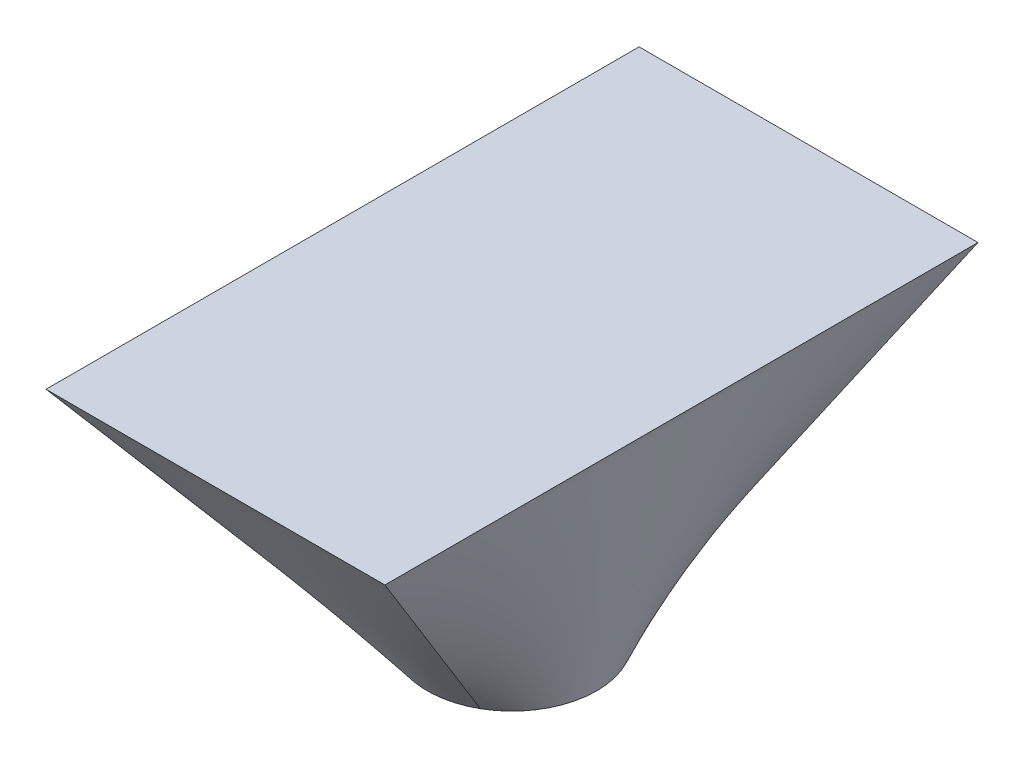
SolidWorks part; units mm, degrees
ref_plane "Front Plane" through (0, 0, 0) normal (0, 0, 1) x (1, 0, 0)
ref_plane "Top Plane" through (0, 0, 0) normal (0, 1, 0) x (1, 0, 0)
ref_plane "Right Plane" through (0, 0, 0) normal (1, 0, 0) x (0, 0, -1)
sketch "Sketch1" plane through (0, 0, 0) normal (0, 1, 0) x (1, 0, 0)
  circle A0 centre (0, 0) radius 3
ref_plane "Plane1" through (0, 10, 0) normal (0, 1, 0) x (1, 0, 0)
sketch "Sketch2" plane through (0, 10, 0) normal (0, 1, 0) x (1, 0, 0)
  line L1 (-6, -10.5) -> (6, -10.5)
  line L2 (-6, -10.5) -> (-6, 10.5)
  line L3 (-6, 10.5) -> (6, 10.5)
  line L4 (6, -10.5) -> (6, 10.5)
  line L5 (-6, -10.5) -> (6, 10.5) construction
  line L6 (-6, 10.5) -> (6, -10.5) construction
  point P0 (0, 0)
loft "Loft2" add profiles "Sketch1", "Sketch2"
sketch "Sketch3" plane through (0, 0, 0) normal (0, 1, 0) x (1, 0, 0)
  circle A0 centre (0, 0) radius 1.4
extrude "Cut-Extrude1" cut sketch "Sketch3" along normal blind 8
